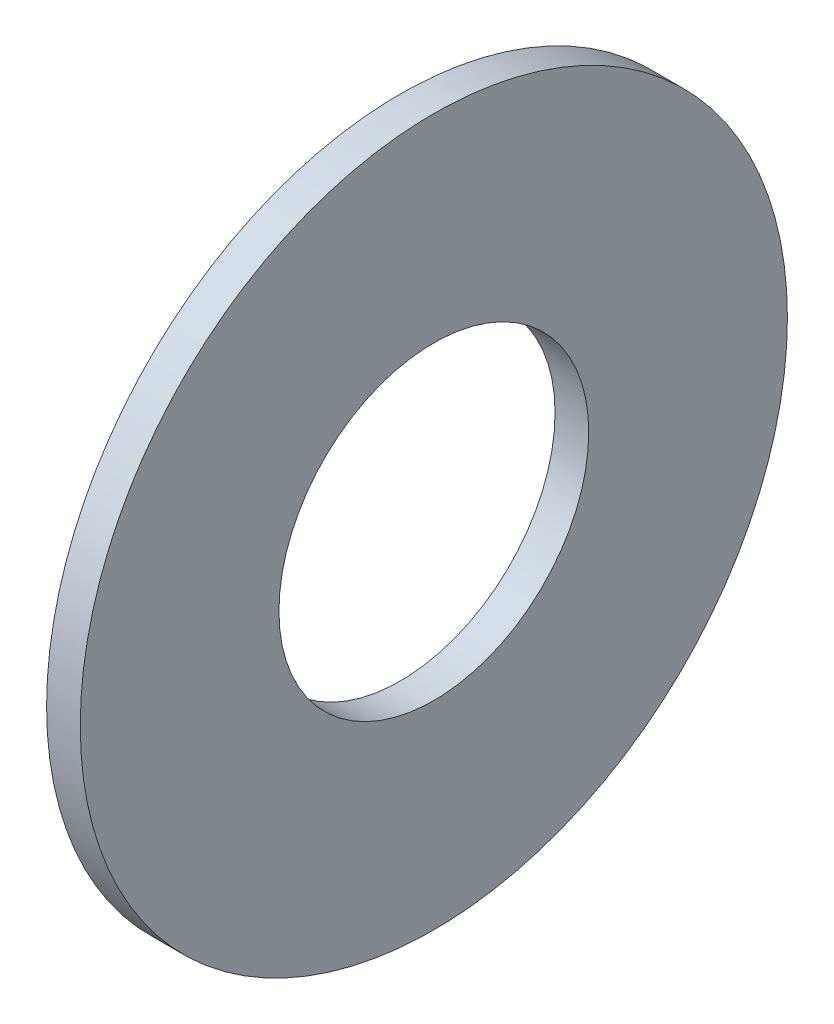
SolidWorks part; units mm, degrees
ref_plane "Plane1" through (0, 0, 0) normal (0, 0, 1) x (1, 0, 0)
ref_plane "Plane2" through (0, 0, 0) normal (0, 1, 0) x (1, 0, 0)
ref_plane "Plane3" through (0, 0, 0) normal (1, 0, 0) x (0, 0, -1)
sketch "Sketch1" plane through (0, 0, 0) normal (1, 0, 0) x (0, 0, -1)
  circle A0 centre (0, 0) radius 4.6
  circle A1 centre (0, 0) radius 10.5
  dimension "Insid_Dia" = 9.2
  dimension "OutsideDia" = 21
extrude "Base-Extrude" add sketch "Sketch1" along normal blind 1
